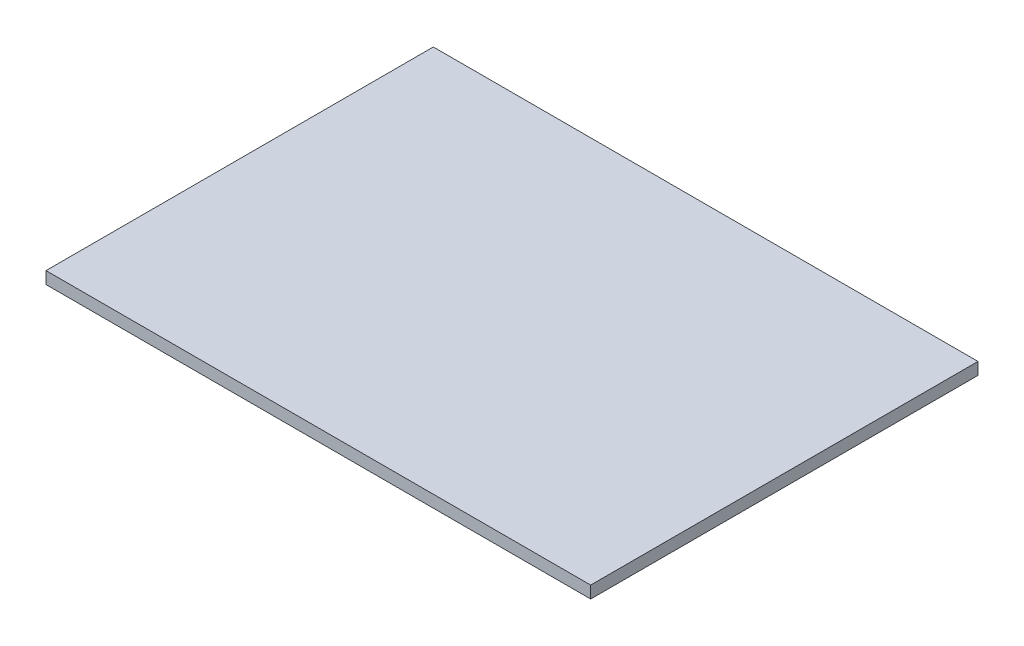
SolidWorks part; units mm, degrees
ref_plane "Alzado" through (0, 0, 0) normal (0, 0, 1) x (1, 0, 0)
ref_plane "Planta" through (0, 0, 0) normal (0, 1, 0) x (1, 0, 0)
ref_plane "Vista lateral" through (0, 0, 0) normal (1, 0, 0) x (0, 0, -1)
sketch "Croquis1" plane through (0, 0, 0) normal (0, 1, 0) x (1, 0, 0)
  line L1 (0, 0) -> (45, 0)
  line L2 (0, 0) -> (0, 32)
  line L3 (0, 32) -> (45, 32)
  line L4 (45, 0) -> (45, 32)
  dimension "D1" = 32
  dimension "D2" = 45
extrude "Saliente-Extruir1" add sketch "Croquis1" along normal blind 1
